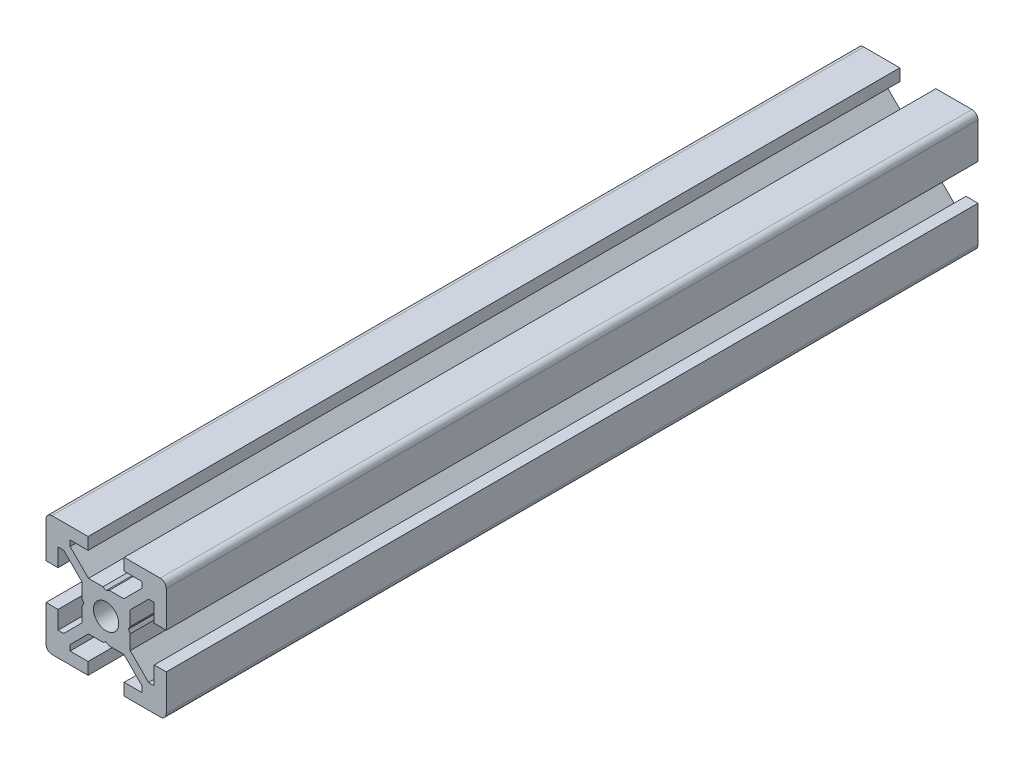
SolidWorks part; units mm, degrees
ref_plane "Front Plane" through (0, 0, 0) normal (0, 0, 1) x (1, 0, 0)
ref_plane "Top Plane" through (0, 0, 0) normal (0, 1, 0) x (1, 0, 0)
ref_plane "Right Plane" through (0, 0, 0) normal (1, 0, 0) x (0, 0, -1)
ref_plane "Plane1" through (0, 0, 0) normal (0, 0, 1) x (1, 0, 0)
sketch "Sketch1" plane through (0, 0, 0) normal (0, 0, 1) x (1, 0, 0)
  line L0 (-10, -3) -> (-10, -9)
  line L1 (-9, -10) -> (-3, -10)
  line L2 (-3, -10) -> (-3, -8)
  line L3 (-3, -8) -> (-6, -8)
  line L4 (-6, -8) -> (-6, -7.0607)
  line L5 (-6, -7.0607) -> (-2.9393, -4)
  line L6 (-2.9393, -4) -> (-0.5196, -4)
  line L7 (-0.5196, -4) -> (0, -3.7)
  line L8 (0, -3.7) -> (0.5196, -4)
  line L9 (0.5196, -4) -> (2.9393, -4)
  line L10 (2.9393, -4) -> (6, -7.0607)
  line L11 (6, -7.0607) -> (6, -8)
  line L12 (6, -8) -> (3, -8)
  line L13 (3, -8) -> (3, -10)
  line L14 (3, -10) -> (9, -10)
  line L15 (10, -9) -> (10, -3)
  line L16 (10, -3) -> (8, -3)
  line L17 (8, -3) -> (8, -6)
  line L18 (8, -6) -> (7.0607, -6)
  line L19 (7.0607, -6) -> (4, -2.9393)
  line L20 (4, -2.9393) -> (4, -0.5196)
  line L21 (4, -0.5196) -> (3.7, 0)
  line L22 (3.7, 0) -> (4, 0.5196)
  line L23 (4, 0.5196) -> (4, 2.9393)
  line L24 (4, 2.9393) -> (7.0607, 6)
  line L25 (7.0607, 6) -> (8, 6)
  line L26 (8, 6) -> (8, 3)
  line L27 (8, 3) -> (10, 3)
  line L28 (10, 3) -> (10, 9)
  line L29 (9, 10) -> (3, 10)
  line L30 (3, 10) -> (3, 8)
  line L31 (3, 8) -> (6, 8)
  line L32 (6, 8) -> (6, 7.0607)
  line L33 (6, 7.0607) -> (2.9393, 4)
  line L34 (2.9393, 4) -> (0.5196, 4)
  line L35 (0.5196, 4) -> (0, 3.7)
  line L36 (0, 3.7) -> (-0.5196, 4)
  line L37 (-0.5196, 4) -> (-2.9393, 4)
  line L38 (-2.9393, 4) -> (-6, 7.0607)
  line L39 (-6, 7.0607) -> (-6, 8)
  line L40 (-6, 8) -> (-3, 8)
  line L41 (-3, 8) -> (-3, 10)
  line L42 (-3, 10) -> (-9, 10)
  line L43 (-10, 9) -> (-10, 3)
  line L44 (-10, 3) -> (-8, 3)
  line L45 (-8, 3) -> (-8, 6)
  line L46 (-8, 6) -> (-7.0607, 6)
  line L47 (-7.0607, 6) -> (-4, 2.9393)
  line L48 (-4, 2.9393) -> (-4, 0.5196)
  line L49 (-4, 0.5196) -> (-3.7, 0)
  line L50 (-3.7, 0) -> (-4, -0.5196)
  line L51 (-4, -0.5196) -> (-4, -2.9393)
  line L52 (-4, -2.9393) -> (-7.0607, -6)
  line L53 (-7.0607, -6) -> (-8, -6)
  line L54 (-8, -6) -> (-8, -3)
  line L55 (-8, -3) -> (-10, -3)
  arc A0 (-10, -9) -> (-9, -10) centre (-9, -9) ccw
  arc A1 (9, -10) -> (10, -9) centre (9, -9) ccw
  arc A2 (10, 9) -> (9, 10) centre (9, 9) ccw
  arc A3 (-9, 10) -> (-10, 9) centre (-9, 9) ccw
extrude "Boss-Extrude1" add sketch "Sketch1" against normal blind 135
ref_plane "Plane2" through (0, 0, 0) normal (1, 0, 0) x (0, 0, -1)
sketch "Sketch2" plane through (0, 0, 0) normal (1, 0, 0) x (0, 0, -1)
  line L0 (0, 0) -> (0, 2.1)
  line L1 (0, 2.1) -> (135, 2.1)
  line L2 (135, 2.1) -> (135, 0)
  line L3 (135, 0) -> (0, 0)
  line L4 (135, 0) -> (0, 0) construction
revolve "Cut-Revolve1" cut sketch "Sketch2" angle 360 about L4
